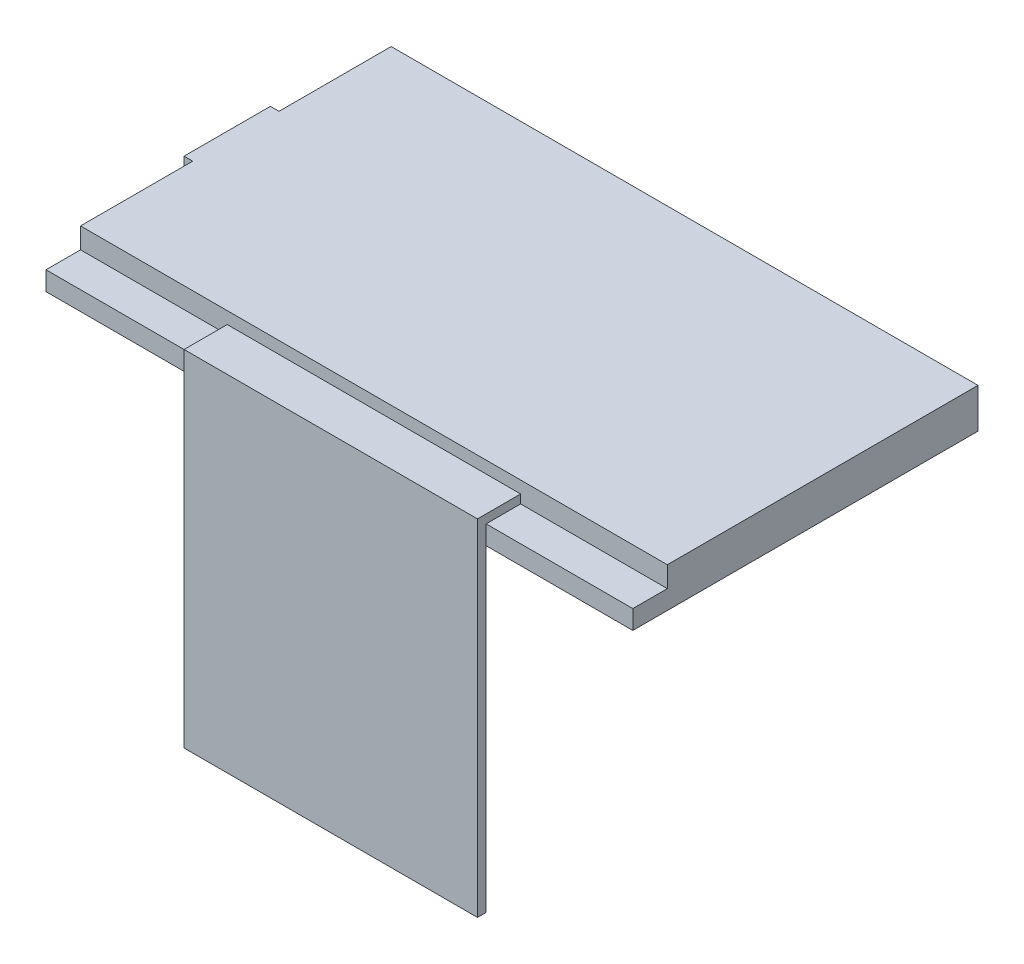
SolidWorks part; units mm, degrees
ref_plane "Front Plane" through (0, 0, 0) normal (0, 0, 1) x (1, 0, 0)
ref_plane "Top Plane" through (0, 0, 0) normal (0, 1, 0) x (1, 0, 0)
ref_plane "Right Plane" through (0, 0, 0) normal (1, 0, 0) x (0, 0, -1)
sketch "Sketch1" plane through (0, 0, 0) normal (0, 1, 0) x (1, 0, 0)
  line L1 (-17, -10) -> (17, -10)
  line L2 (-17, -10) -> (-17, 10)
  line L3 (-17, 10) -> (17, 10)
  line L4 (17, -10) -> (17, 10)
  line L5 (-17, -10) -> (17, 10) construction
  line L6 (-17, 10) -> (17, -10) construction
  point P0 (0, 0)
  dimension "D1" = 34
  dimension "D2" = 20
extrude "Boss-Extrude1" add sketch "Sketch1" along normal blind 1.1
sketch "Sketch3" plane through (0, 1.1, 0) normal (0, 1, 0) x (1, 0, 0)
  line L0 (17, -10) -> (17, 10) construction
  line L1 (-17, 10) -> (17, 10)
  line L2 (-17, 10) -> (-17, -8)
  line L3 (-17, -8) -> (17, -8)
  line L4 (17, 10) -> (17, -8)
  dimension "D1" = 18
extrude "Boss-Extrude2" add sketch "Sketch3" along normal blind 1.2
sketch "Sketch4" plane through (-17, 0, 0) normal (-1, 0, 0) x (0, 0, 1)
  line L0 (-10, 0) -> (10, 0) construction
  line L1 (-3.5, 0) -> (1.5, 0)
  line L2 (-3.5, 0) -> (-3.5, 2.3)
  line L3 (-3.5, 2.3) -> (1.5, 2.3)
  line L4 (1.5, 0) -> (1.5, 2.3)
  line L5 (-10, 2.3) -> (8, 2.3) construction
  point P8 (-1, 2.3)
  point P9 (-1, 2.3)
  dimension "D1" = 5
extrude "Boss-Extrude3" add sketch "Sketch4" along normal blind 0.5
sketch "Sketch5" plane through (0, 1.1, 0) normal (0, 1, 0) x (1, 0, 0)
  line L0 (-17, -10) -> (17, -10) construction
  line L1 (-8.5, -10) -> (8.5, -10)
  line L2 (-8.5, -10) -> (-8.5, -8)
  line L3 (-8.5, -8) -> (8.5, -8)
  line L4 (8.5, -10) -> (8.5, -8)
  line L5 (-17, -8) -> (17, -8) construction
  point P8 (0, -10)
  point P9 (0, -10)
  dimension "D1" = 17
extrude "Boss-Extrude4" add sketch "Sketch5" along normal blind 0.5
sketch "Sketch6" plane through (0, 1.6, 0) normal (0, 1, 0) x (1, 0, 0)
  line L1 (-8.5, -10) -> (8.5, -10)
  line L2 (-8.5, -10) -> (-8.5, -10.5)
  line L3 (-8.5, -10.5) -> (8.5, -10.5)
  line L4 (8.5, -10) -> (8.5, -10.5)
  dimension "D1" = 0.5
extrude "Boss-Extrude5" add sketch "Sketch6" against normal blind 20
